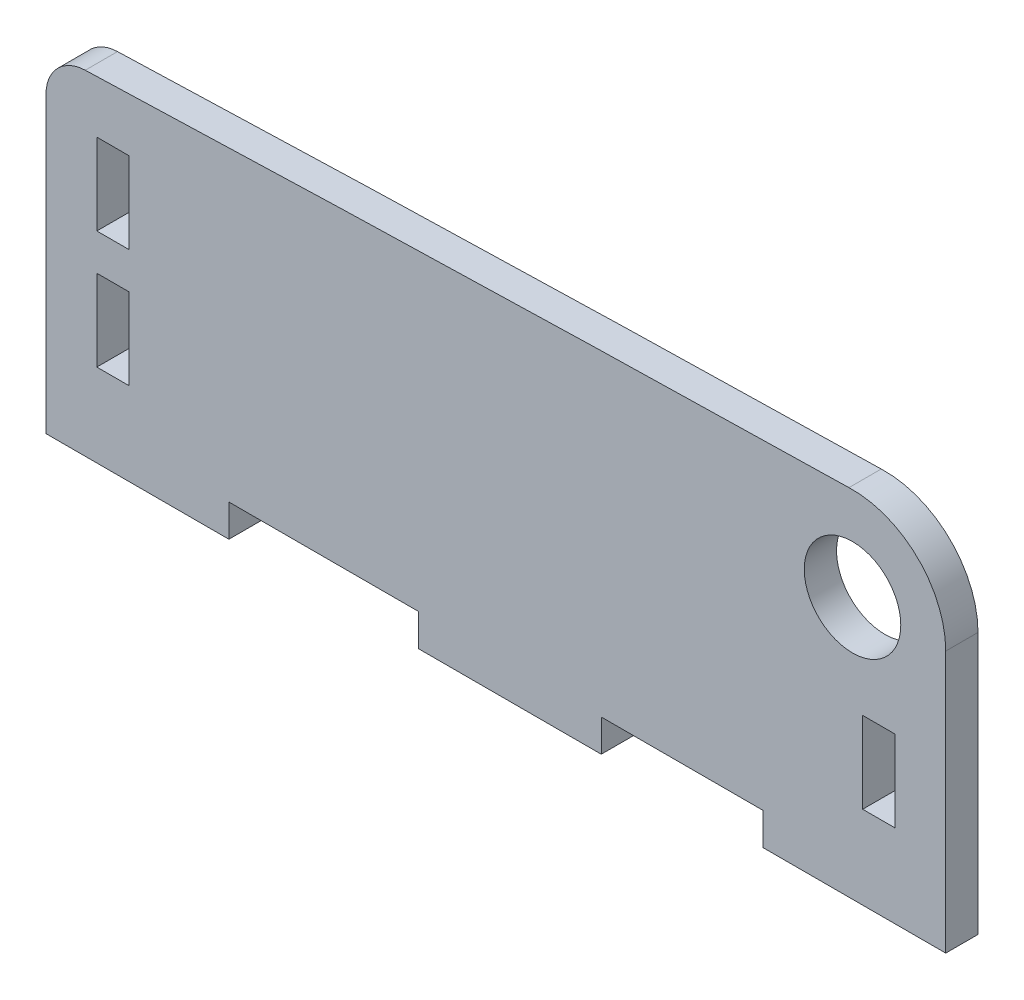
SolidWorks part; units mm, degrees
ref_plane "Front Plane" through (0, 0, 0) normal (0, 0, 1) x (1, 0, 0)
ref_plane "Top Plane" through (0, 0, 0) normal (0, 1, 0) x (1, 0, 0)
ref_plane "Right Plane" through (0, 0, 0) normal (1, 0, 0) x (0, 0, -1)
sketch "Sketch1" plane through (0, 0, 0) normal (0, 0, 1) x (1, 0, 0)
  line L1 (-26.416, -9.8) -> (26.416, -9.8)
  line L2 (-26.416, -9.8) -> (-26.416, 9.8)
  line L3 (-26.416, 9.8) -> (26.416, 9.8)
  line L4 (26.416, -9.8) -> (26.416, 9.8)
  line L5 (-26.416, -9.8) -> (26.416, 9.8) construction
  line L6 (-26.416, 9.8) -> (26.416, -9.8) construction
  line L7 (-20.15, -9.8) -> (20.15, -9.8)
  line L8 (-20.15, -9.8) -> (-20.15, 9.8)
  line L9 (-20.15, 9.8) -> (20.15, 9.8)
  line L10 (20.15, -9.8) -> (20.15, 9.8)
  line L11 (-20.15, -9.8) -> (20.15, 9.8) construction
  line L12 (-20.15, 9.8) -> (20.15, -9.8) construction
  line L13 (-26.416, 9.8) -> (26.416, 9.8)
  line L14 (-26.416, 9.8) -> (-26.416, 14.8)
  line L15 (-26.416, 14.8) -> (26.416, 14.8)
  line L16 (26.416, 9.8) -> (26.416, 14.8)
  line L17 (26.416, -9.8) -> (-26.416, -9.8)
  line L18 (26.416, -9.8) -> (26.416, -14.8)
  line L19 (26.416, -14.8) -> (-26.416, -14.8)
  line L20 (-26.416, -9.8) -> (-26.416, -14.8)
  circle A0 centre (-23.95, -4.974) radius 1.675
  circle A1 centre (-23.95, 4.974) radius 1.675
  circle A2 centre (23.95, 4.974) radius 1.675
  circle A3 centre (23.95, -4.974) radius 1.675
  point P0 (0, 0)
  point P14 (0, 0)
  dimension "D1" = 3.35
  dimension "D2" = 3.35
  dimension "D3" = 3.35
  dimension "D4" = 3.35
  dimension "D7" = 4.826
  dimension "D8" = 3.8
  dimension "D9" = 3.8
  dimension "D10" = 4.826
  dimension "D11" = 4.826
  dimension "D12" = 4.826
  dimension "D13" = 3.8
  dimension "D5" = 19.6
  dimension "D6" = 52.832
  dimension "D15" = 40.3
  dimension "D16" = 5
  dimension "D17" = 5
  dimension "3.9" = 3.8
extrude "Boss-Extrude2" add sketch "Sketch1" along normal blind 3.175 contours L1 L8 L3 L2 A1 A0 | L10 L1 L4 L3 A3 A2 | L14 L13 L16 L15 | L18 L17 L20 L19
sketch "Sketch3" plane through (0, 0, 3.175) normal (0, 0, 1) x (1, 0, 0)
  line L0 (26.416, -14.8) -> (56.416, -14.8)
  line L6 (26.416, 14.8) -> (56.416, 14.8)
  line L7 (26.416, 14.8) -> (26.416, -14.906)
  line L8 (26.416, -14.906) -> (56.416, -14.906)
  line L9 (56.416, 14.8) -> (56.416, -14.906)
  line M3 (26.416, -14.8) -> (26.416, 14.8)
  dimension "D2" = 30
extrude "Boss-Extrude3" add sketch "Sketch3" against normal up to surface (3.175 mm away) contours L9 L6 L0 M3 up to face at (0, 0, 0)
sketch "Sketch4" plane through (0, 0, 0) normal (0, 0, -1) x (-1, 0, 0)
  line L3 (-56.416, 14.8) -> (-56.416, -14.8) construction
  line L4 (-56.416, -14.8) -> (26.416, -14.8) construction
  circle A0 centre (-40.576, 7.77) radius 4.75
  dimension "D1" = 15.84
  dimension "D2" = 22.57
  dimension "D3" = 9.5
extrude "Cut-Extrude1" cut sketch "Sketch4" against normal blind 10 contours A0
sketch "Sketch22" plane through (0, 0, 0) normal (0, 0, -1) x (-1, 0, 0)
  line L0 (-52.3294, 14.8) -> (-30.0917, 14.8)
  line L1 (26.416, 14.8) -> (-56.416, 14.8) construction
  circle A0 centre (-40.576, 7.77) radius 9.175
  dimension "D1" = 18.35
extrude "Boss-Extrude14" add sketch "Sketch22" against normal up to surface (3.175 mm away) contours L0 A0
sketch "Sketch23" plane through (0, 0, 0) normal (0, 0, -1) x (-1, 0, 0)
  line L0 (-49.751, 7.77) -> (-49.751, -14.8)
  line L1 (-56.416, -14.8) -> (26.416, -14.8) construction
  circle A0 centre (-40.576, 7.77) radius 9.175
  line M4 (-46.4717, 14.8) -> (-56.416, 14.8)
  line M5 (-56.416, 14.8) -> (-56.416, -14.8)
  line M6 (-56.416, -14.8) -> (26.416, -14.8)
extrude "Cut-Extrude8" cut sketch "Sketch23" against normal blind 10 contours A0 L0 M4 M5 M6
sketch "Sketch24" plane through (0, 0, 0) normal (0, 0, -1) x (-1, 0, 0)
  line L0 (25.625, 4.974) -> (25.625, 17.1862)
  line L1 (21.4452, -14.8) -> (27.751, -14.8)
  line L2 (-49.751, -14.8) -> (26.416, -14.8) construction
  line L3 (26.416, 14.8) -> (-34.6803, 14.8) construction
  line L4 (25.625, 14.8) -> (30.625, 14.8)
  line L5 (25.625, 14.8) -> (25.625, -14.8)
  line L6 (25.625, -14.8) -> (30.625, -14.8)
  line L7 (30.625, 14.8) -> (30.625, -14.8)
  circle A0 centre (23.95, 4.974) radius 1.675 construction
  line M14 (26.416, -14.8) -> (26.416, 14.8)
  dimension "D1" = 5
extrude "Boss-Extrude15" add sketch "Sketch24" against normal up to surface (3.175 mm away) contours L7 L4 L1 L6 M14 up to face at (45.326, 7.77, 3.175)
sketch "Sketch25" plane through (0, 0, 0) normal (0, 0, -1) x (-1, 0, 0)
  line L0 (30.625, 14.8) -> (30.625, -14.8) construction
  line L1 (30.625, 9.8) -> (33.8, 9.8)
  line L2 (30.625, 9.8) -> (30.625, 1.8)
  line L3 (30.625, 1.8) -> (33.8, 1.8)
  line L4 (33.8, 9.8) -> (33.8, 1.8)
  line L5 (28.9462, -14.8) -> (31.8791, -14.8)
  line L6 (30.625, -1.8) -> (33.8, -1.8)
  line L7 (30.625, -1.8) -> (30.625, -9.8)
  line L8 (30.625, -9.8) -> (33.8, -9.8)
  line L9 (33.8, -1.8) -> (33.8, -9.8)
  line L10 (-49.751, -14.8) -> (30.625, -14.8) construction
  line L12 (30.625, 14.8) -> (38.8, 14.8)
  line L13 (30.625, 14.8) -> (30.625, -14.8)
  line L14 (30.625, -14.8) -> (38.8, -14.8)
  line L15 (38.8, 14.8) -> (38.8, -14.8)
  line M23 (30.625, -14.8) -> (30.625, 14.8)
  dimension "D1" = 3.175
  dimension "D2" = 3.175
  dimension "D3" = 8
  dimension "D4" = 8
  dimension "D5" = 5
  dimension "D6" = 0
  dimension "D7" = 8.175
  dimension "D8" = 5
extrude "Boss-Extrude16" add sketch "Sketch25" against normal up to surface (3.175 mm away) contours L15 L12 L1 L4 L3 L6 L9 L8 L5 L14 M23 up to face at (45.326, 7.77, 3.175)
sketch "Sketch26" plane through (0, 0, 0) normal (0, 0, -1) x (-1, 0, 0)
  line L0 (-34.6803, 14.8) -> (38.8, 14.8)
  arc A0 (-40.576, 16.945) -> (38.8, 14.8) centre (-135.5308, -4966.6007) cw
  arc A1 (-34.6803, 14.8) -> (-49.751, 7.77) centre (-40.576, 7.77) ccw construction
  circle A2 centre (-40.576, 7.77) radius 9.175
  arc M18 (-34.6803, 14.8) -> (-49.751, 7.77) centre (-40.576, 7.77) ccw
  line M22 (38.8, 14.8) -> (-34.6803, 14.8)
extrude "Boss-Extrude17" add sketch "Sketch26" against normal up to surface (3.175 mm away) contours A0 M18 M22 up to face at (-32.2125, 5.8, 3.175)
fillet "Fillet5" radius 4 1 edges at (-38.8, 14.8, 1.5875)
sketch "Sketch27" plane through (0, 0, 0) normal (0, 0, -1) x (-1, 0, 0)
  line L0 (-49.751, -14.8) -> (38.8, -14.8) construction
  line L1 (-44.751, -9.8) -> (-41.576, -9.8)
  line L2 (-44.751, -9.8) -> (-44.751, -1.8)
  line L3 (-44.751, -1.8) -> (-41.576, -1.8)
  line L4 (-41.576, -9.8) -> (-41.576, -1.8)
  line L5 (-49.751, 7.77) -> (-49.751, -14.8) construction
  dimension "D1" = 3.175
  dimension "D2" = 8
  dimension "D3" = 5
  dimension "D4" = 5
extrude "Cut-Extrude9" cut sketch "Sketch27" against normal blind 10
sketch "Sketch28" plane through (0, 0, 0) normal (0, 0, -1) x (-1, 0, 0)
  line L0 (-49.751, -14.8) -> (38.8, -14.8) construction
  line L1 (-49.751, -14.8) -> (-31.751, -14.8)
  line L2 (-49.751, -14.8) -> (-49.751, -17.975)
  line L3 (-49.751, -17.975) -> (-31.751, -17.975)
  line L4 (-31.751, -14.8) -> (-31.751, -17.975)
  line L5 (-15.85, -14.8) -> (2.15, -14.8)
  line L6 (-15.85, -14.8) -> (-15.85, -17.975)
  line L7 (-15.85, -17.975) -> (2.15, -17.975)
  line L8 (2.15, -14.8) -> (2.15, -17.975)
  line L9 (38.8, 10.936) -> (38.8, -14.8) construction
  line L10 (20.8, -14.8) -> (38.8, -14.8)
  line L11 (20.8, -14.8) -> (20.8, -17.975)
  line L12 (20.8, -17.975) -> (38.8, -17.975)
  line L13 (38.8, -14.8) -> (38.8, -17.975)
  dimension "D1" = 3.175
  dimension "D2" = 3.175
  dimension "D3" = 3.175
  dimension "D4" = 18
  dimension "D5" = 18
  dimension "D6" = 18
  dimension "D7" = 0
  dimension "D8" = 18.65
extrude "Boss-Extrude18" add sketch "Sketch28" against normal up to surface (3.175 mm away) contours L2 L1 L4 L3 | L6 L5 L8 L7 | L11 L10 L13 L12 up to face at (43.1635, -5.8, 3.175)
sketch "Sketch29" plane through (0, 0, 0) normal (0, 0, -1) x (-1, 0, 0)
  line L1 (-26.5134, -10.9888) -> (27.3004, -10.9888)
  line L2 (-26.5134, -10.9888) -> (-26.5134, 12.487)
  line L3 (-26.5134, 12.487) -> (27.3004, 12.487)
  line L4 (27.3004, -10.9888) -> (27.3004, 12.487)
extrude "Boss-Extrude19" add sketch "Sketch29" against normal up to surface (3.175 mm away) up to face at (43.1635, -5.8, 3.175)
sketch "Sketch30" plane through (0, 0, 0) normal (0, 0, -1) x (-1, 0, 0)
  circle A0 centre (-40.576, 7.77) radius 4.75
